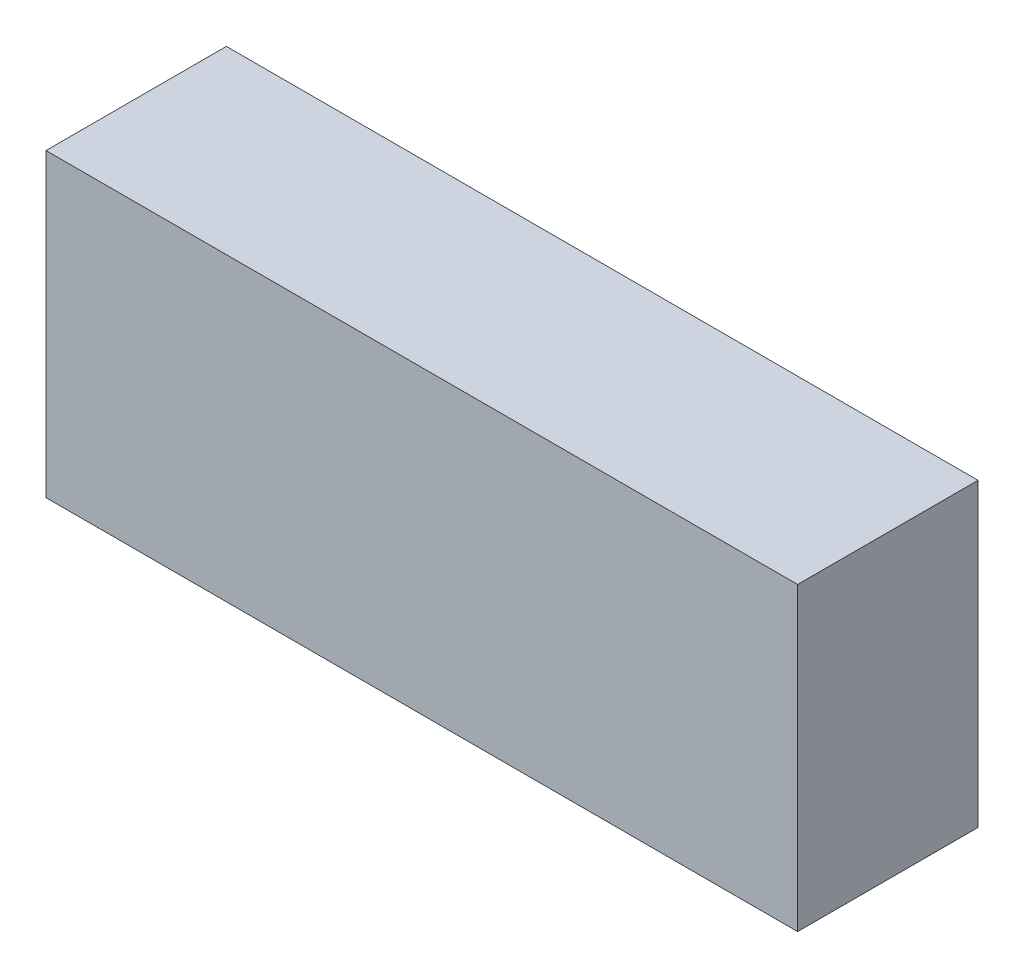
SolidWorks part; units mm, degrees
ref_plane "정면" through (0, 0, 0) normal (0, 0, 1) x (1, 0, 0)
ref_plane "윗면" through (0, 0, 0) normal (0, 1, 0) x (1, 0, 0)
ref_plane "우측면" through (0, 0, 0) normal (1, 0, 0) x (0, 0, -1)
sketch "스케치1" plane through (0, 0, 0) normal (0, 0, 1) x (1, 0, 0)
  line L1 (12.5, -5) -> (-12.5, -5)
  line L2 (12.5, -5) -> (12.5, 5)
  line L3 (12.5, 5) -> (-12.5, 5)
  line L4 (-12.5, -5) -> (-12.5, 5)
  line L5 (12.5, -5) -> (-12.5, 5) construction
  line L6 (12.5, 5) -> (-12.5, -5) construction
  point P0 (0, 0)
  dimension "D1" = 10
  dimension "D2" = 25
extrude "보스-돌출1" add sketch "스케치1" along normal blind 6 contours L3 L4 L1 L2
